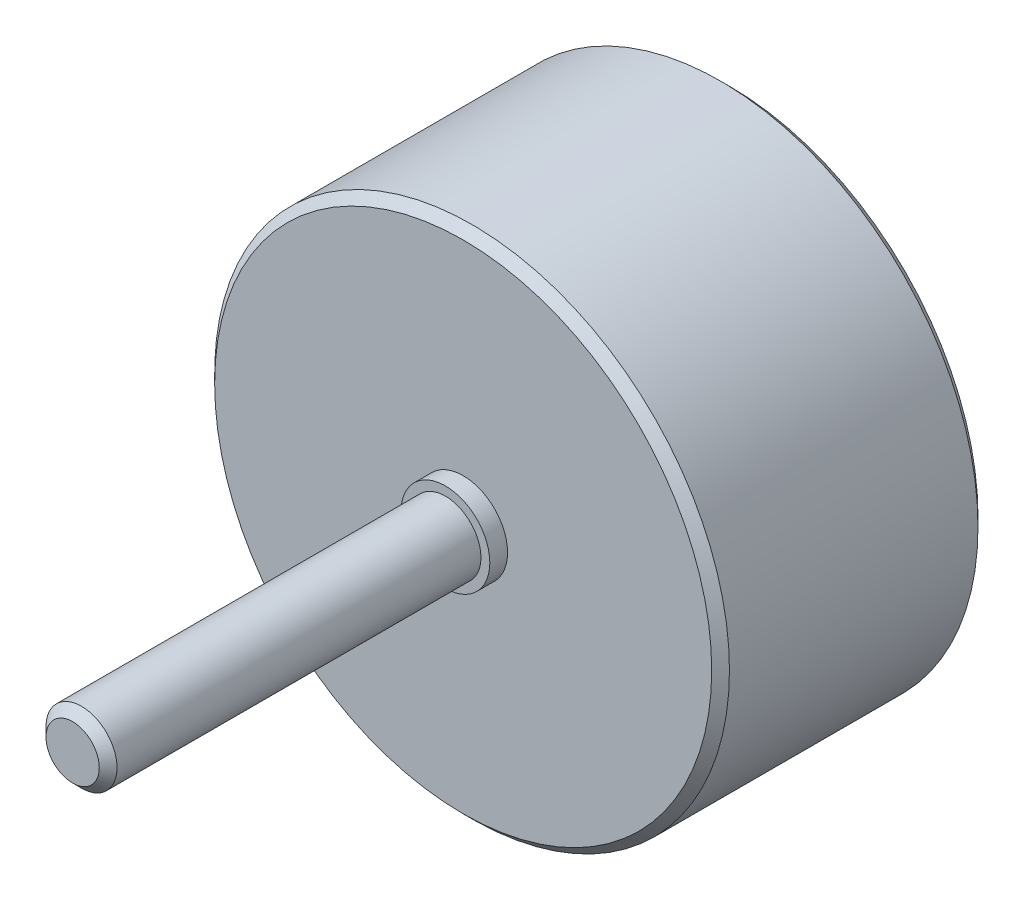
SolidWorks part; units mm, degrees
ref_plane "Plan de face" through (0, 0, 0) normal (0, 0, 1) x (1, 0, 0)
ref_plane "Plan de dessus" through (0, 0, 0) normal (0, 1, 0) x (1, 0, 0)
ref_plane "Plan de droite" through (0, 0, 0) normal (1, 0, 0) x (0, 0, -1)
sketch "Esquisse1" plane through (0, 0, 0) normal (0, 0, 1) x (1, 0, 0)
  circle A0 centre (0, 0) radius 29
extrude "Boss.-Extru.1" add sketch "Esquisse1" along normal blind 30
sketch "Esquisse2" plane through (0, 0, 30) normal (0, 0, 1) x (1, 0, 0)
  circle A0 centre (0, 0) radius 4
  dimension "D1" = 8
extrude "Boss.-Extru.2" add sketch "Esquisse2" along normal blind 6 contours A0
sketch "Esquisse3" plane through (0, 0, 30) normal (0, 0, 1) x (1, 0, 0)
  circle A0 centre (0, 0) radius 5
extrude "Boss.-Extru.3" add sketch "Esquisse3" along normal blind 2
sketch "Esquisse4" plane through (0, 0, 0) normal (0, 0, -1) x (-1, 0, 0)
  circle A0 centre (0, 0) radius 4
extrude "Enlèv. mat.-Extru.1" cut sketch "Esquisse4" against normal blind 5
chamfer "Chanfrein1" distance 1 angle 45 2 edges at (29, 0, 30) (29, 0, 0)
sketch "Esquisse5" plane through (0, 0, 36) normal (0, 0, 1) x (1, 0, 0)
  circle A0 centre (0, 0) radius 4
extrude "Boss.-Extru.4" add sketch "Esquisse5" along normal blind 10
sketch "Esquisse6" plane through (0, 0, 46) normal (0, 0, 1) x (1, 0, 0)
  circle A0 centre (0, 0) radius 4
extrude "Boss.-Extru.5" add sketch "Esquisse6" along normal blind 28
chamfer "Chanfrein2" distance 1 angle 45 1 edges at (4, 0, 74)
